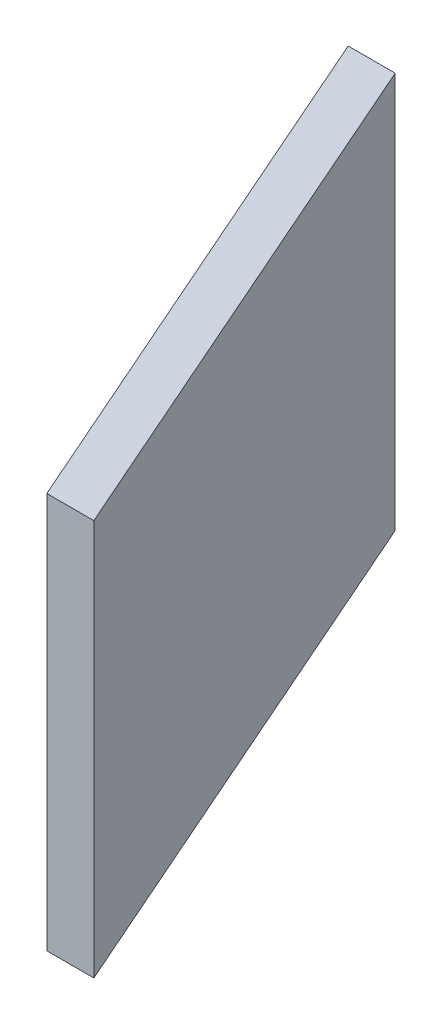
SolidWorks part; units mm, degrees
ref_plane "Front Plane" through (0, 0, 0) normal (0, 0, 1) x (1, 0, 0)
ref_plane "Top Plane" through (0, 0, 0) normal (0, 1, 0) x (1, 0, 0)
ref_plane "Right Plane" through (0, 0, 0) normal (1, 0, 0) x (0, 0, -1)
sketch "Sketch1" plane through (0, 0, 0) normal (0, 1, 0) x (1, 0, 0)
  line L0 (0, 0) -> (-11.0003, 25)
  line L1 (-11.0003, 25) -> (-8.8152, 25)
  line L2 (-8.8152, 25) -> (2.185, 0)
  line L3 (2.185, 0) -> (0, 0)
  dimension "D1" = 2
  dimension "D2" = 25
  dimension "D3" = 66.25
extrude "Boss-Extrude1" add sketch "Sketch1" along normal blind 18.4
